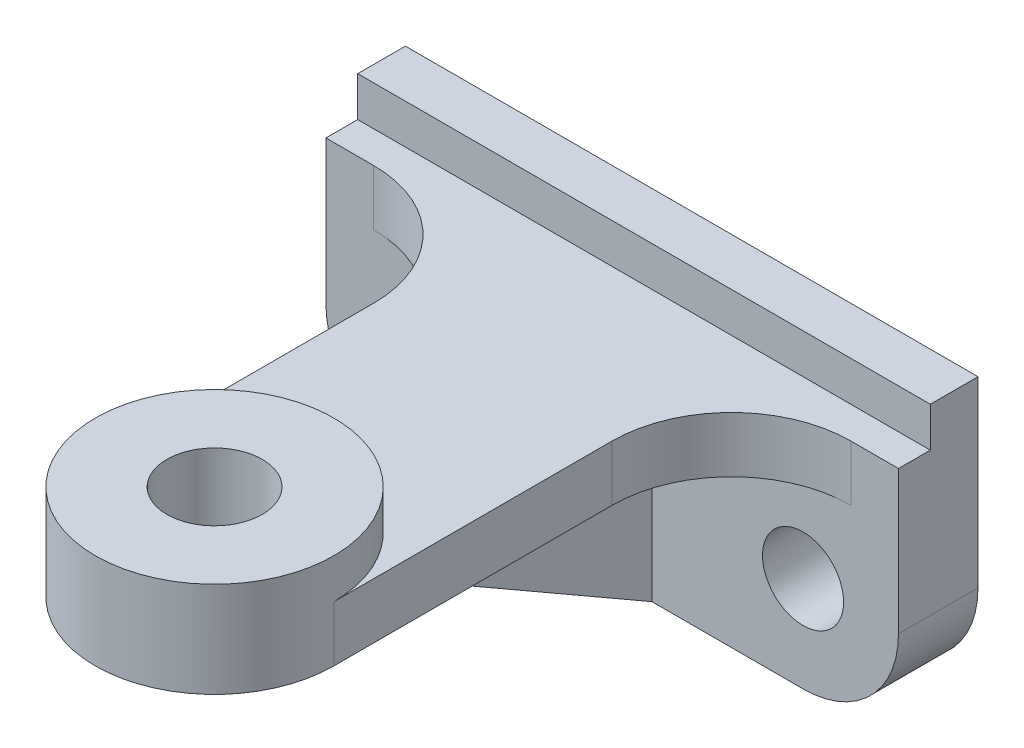
SolidWorks part; units mm, degrees
material "1.0044 (S275JR)"
ref_plane "Alzado" through (0, 0, 0) normal (0, 0, 1) x (1, 0, 0)
ref_plane "Planta" through (0, 0, 0) normal (0, 1, 0) x (1, 0, 0)
ref_plane "Vista lateral" through (0, 0, 0) normal (1, 0, 0) x (0, 0, -1)
sketch "Croquis1" plane through (0, 0, 0) normal (0, 0, 1) x (1, 0, 0)
  line L1 (-36, 17.5) -> (36, 17.5)
  line L2 (-36, 17.5) -> (-36, -17.5)
  line L3 (-36, -17.5) -> (36, -17.5)
  line L4 (36, 17.5) -> (36, -17.5)
  line L5 (-36, 17.5) -> (36, -17.5) construction
  line L6 (-36, -17.5) -> (36, 17.5) construction
  circle A0 centre (-24, -5.5) radius 5.1
  circle A1 centre (24, -5.5) radius 5.1
  point P0 (0, 0)
  dimension "D3" = 48
  dimension "D4" = 12
  dimension "D5" = 12
  dimension "D1" = 72
  dimension "D2" = 35
extrude "Saliente-Extruir1" add sketch "Croquis1" along normal blind 10
fillet "Redondeo1" radius 12 2 edges at (36, -17.5, 5) (-36, -17.5, 5)
sketch "Croquis2" plane through (-36, 0, 0) normal (-1, 0, 0) x (0, 0, 1)
  line L0 (10, 17.5) -> (6, 17.5)
  line L1 (10, 17.5) -> (0, 17.5) construction
  line L2 (6, 17.5) -> (6, 12.5)
  line L3 (6, 12.5) -> (10, 12.5)
  line L4 (10, 17.5) -> (10, -5.5) construction
  line L5 (10, 12.5) -> (10, 17.5)
extrude "Cortar-Extruir1" cut sketch "Croquis2" against normal up to body
sketch "Croquis3" plane through (0, 12.5, 0) normal (0, 1, 0) x (1, 0, 0)
  line L5 (36, -10) -> (-36, -10) construction
  line L6 (15, -60) -> (15, -10)
  line L7 (15, -10) -> (-15, -10)
  line L8 (-15, -10) -> (-15, -60)
  arc A5 (-15, -60) -> (15, -60) centre (0, -60) ccw
  circle A6 centre (0, -60) radius 6
extrude "Saliente-Extruir2" add sketch "Croquis3" against normal blind 7
sketch "Croquis5" plane through (0, 12.5, 0) normal (0, 1, 0) x (1, 0, 0)
  circle A0 centre (0, -60) radius 6
  circle A1 centre (0, -60) radius 15
extrude "Saliente-Extruir4" add sketch "Croquis5" along normal blind 5
fillet "Redondeo2" radius 15 2 edges at (-15, 9, 10) (15, 9, 10)
sketch "Croquis8" plane through (0, 0, 0) normal (1, 0, 0) x (0, 0, -1)
  line L4 (-10, -17.5) -> (-50, 5.5)
  line L5 (-60, 5.5) -> (-25, 5.5) construction
  dimension "D1" = 40
rib "Nervio31" sketch "Croquis8" sketch "Croquis8" thickness 10 extrusion direction parallel to sketch draft on no parameters "D1"=10
